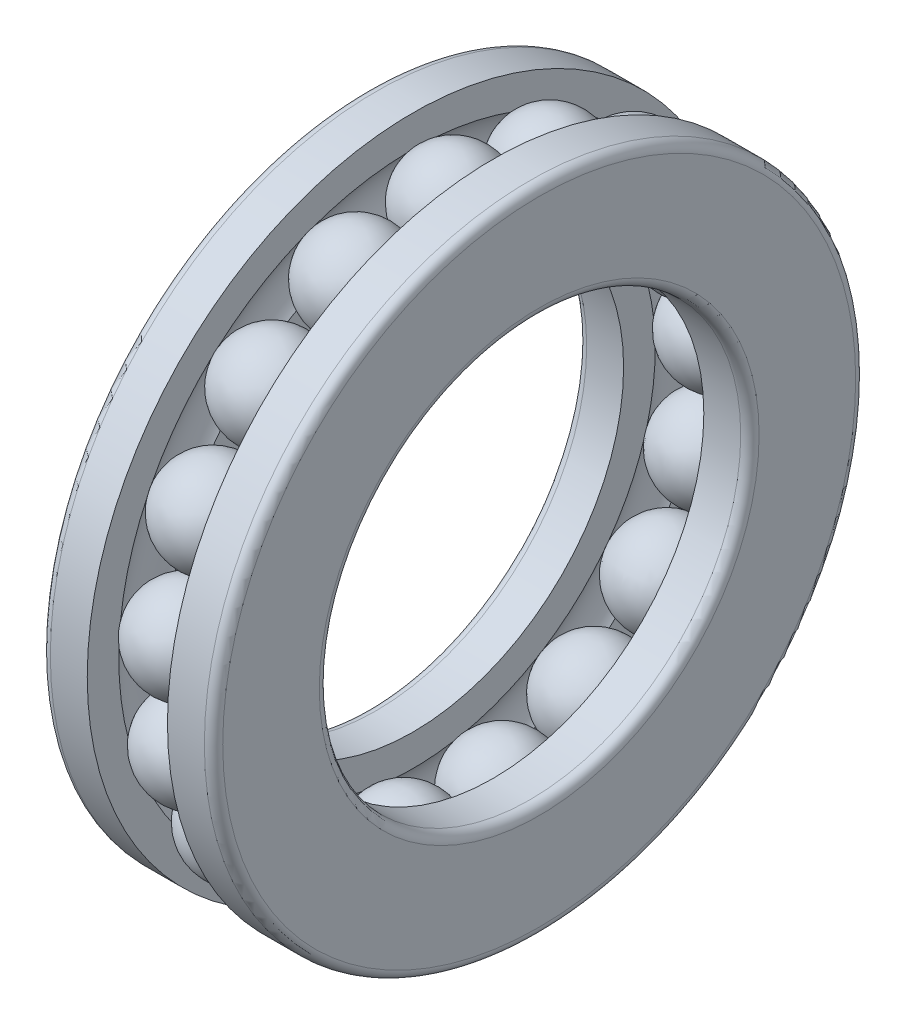
SolidWorks part; units mm, degrees
ref_plane "Plane1" through (0, 0, 0) normal (0, 0, 1) x (1, 0, 0)
ref_plane "Plane2" through (0, 0, 0) normal (0, 1, 0) x (1, 0, 0)
ref_plane "Plane3" through (0, 0, 0) normal (1, 0, 0) x (0, 0, -1)
sketch "Clipboard" plane through (0, 0, 0) normal (0, 0, 1) x (1, 0, 0)
  line L0 (-10, 0) -> (10, 0) construction
  line L1 (0, 0) -> (21.3836, -6.5376)
  line L2 (0, 0) -> (27.3662, 35.0271)
  line L3 (0, 0) -> (13.7666, -17.6205)
  line L4 (0, 0) -> (-22.3471, -0.7804)
  dimension "BallCLRad" = 44.45
  dimension "Count" = 52
  dimension "Show_count" = 52
  dimension "Max_count" = 17
  dimension "Min_count" = 2
sketch "InnRacSke" plane through (0, 0, 0) normal (0, 0, 1) x (1, 0, 0)
  line L0 (-6.6469, 40.1581) -> (-6.6469, 34.925)
  line L1 (-6.6469, 34.925) -> (-12.7635, 34.925)
  line L2 (-14.2875, 36.449) -> (-14.2875, 52.451)
  line L3 (-12.7635, 53.975) -> (-6.6469, 53.975)
  line L4 (-6.6469, 53.975) -> (-6.6469, 48.7419)
  line L5 (-34.925, 0) -> (34.925, 0) construction
  line L6 (0, 0) -> (0, 25.4) construction
  arc A0 (-12.7635, 34.925) -> (-14.2875, 36.449) centre (-12.7635, 36.449) cw
  arc A1 (-14.2875, 52.451) -> (-12.7635, 53.975) centre (-12.7635, 52.451) cw
  arc A2 (-6.6469, 48.7419) -> (-6.6469, 40.1581) centre (0, 44.45) ccw
  dimension "BallCLRad" = 44.45
  dimension "Ball_diameter" = 15.8242
  dimension "ID" = 69.85
  dimension "OD" = 107.95
  dimension "Width" = 28.575
  dimension "gap" = 13.2937
revolve "Race" add sketch "InnRacSke" angle 360 about L5
ref_axis "Axis1" through (-50, 0, 0) along (1, 0, 0)
sketch "BalDetSke" plane through (0, 0, 0) normal (0, 0, 1) x (1, 0, 0)
  line L0 (-7.9375, 44.45) -> (7.9375, 44.45)
  line L1 (-14.5732, 44.45) -> (14.5732, 44.45) construction
  arc A0 (7.9375, 44.45) -> (-7.9375, 44.45) centre (0, 44.45) cw
  dimension "BallCLRad" = 44.45
  dimension "Ball_diameter" = 15.875
revolve "BallDetailed" add sketch "BalDetSke" angle 360 about L1
sketch "BalSimSke" plane through (0, 0, 0) normal (0, 0, 1) x (1, 0, 0)
  line L0 (-25.4, 0) -> (25.4, 0) construction
  circle A0 centre (0, 44.45) radius 7.9375
  dimension "BallCLRad" = 44.45
  dimension "Ball_diameter" = 15.875
revolve "BallsSimplified" [suppressed] add sketch "BalSimSke" angle 360 about L0
mirror "Mirror1" about plane through (0, 0, 0) normal (1, 0, 0) of "Race"
pattern_circular "BallsDetailed" count 17 every 21.176 about axis through (-50, 0, 0) along (1, 0, 0) of "BallDetailed"
sketch "CagSpiSke" plane through (0, 0, 0) normal (0, 0, 1) x (1, 0, 0)
  line L0 (1.9844, 35.7188) -> (1.9844, 53.1812)
  line L1 (1.9844, 53.1812) -> (-1.9844, 53.1812)
  line L2 (-1.9844, 53.1812) -> (-1.9844, 35.7188)
  line L3 (-1.9844, 35.7188) -> (1.9844, 35.7188)
  line L4 (-34.925, 0) -> (34.925, 0) construction
  line L5 (0, 0) -> (0, 50.8) construction
  dimension "Thickness" = 3.9688
  dimension "ID" = 71.4375
  dimension "OD" = 106.3625
revolve "CageSpine" [suppressed] add sketch "CagSpiSke" angle 360 about L4
equation "\"BallCLRad@Clipboard\" =  ( \"OD@InnRacSke\" + \"ID@InnRacSke\" )  / 4"
equation "\"BallCLRad@BalSimSke\" = \"BallCLRad@Clipboard\""
equation "\"BallCLRad@BalDetSke\" = \"BallCLRad@Clipboard\""
equation "\"BallCLRad@InnRacSke\" = \"BallCLRad@Clipboard\""
equation "\"Ball_diameter@InnRacSke\" = \"Ball_diameter@BalDetSke\" - 0.002"
equation "\"Ball_diameter@BalSimSke\" = \"Ball_diameter@BalDetSke\""
equation "\"Max_count@Clipboard\" = int( 3.14159265 / atn(( \"Ball_diameter@BalDetSke\" / 2) / sqr( \"BallCLRad@Clipboard\"  *  \"BallCLRad@Clipboard\" - ( \"Ball_diameter@BalDetSke\" / 2) *  ( \"Ball_diameter@BalDetSke\" / 2))))"
equation "\"Max_count@Clipboard\" = ((sgn( \"Max_count@Clipboard\" - \"Count@Clipboard\" )-1)*( \"Max_count@Clipboard\" - \"Count@Clipboard\" ))/-2+ \"Count@Clipboard\""
equation "\"Count@BallsDetailed\" = int( \"Show_count@Clipboard\" ) "
equation "\"Count@BallsDetailed\" = ((sgn( \"Count@BallsDetailed\" - \"Max_count@Clipboard\" )-1)*( \"Count@BallsDetailed\" - \"Max_count@Clipboard\" ))/-2+ \"Max_count@Clipboard\""
equation "\"Count@BallsDetailed\" = ((sgn( \"Count@BallsDetailed\" - \"Min_count@Clipboard\" )+1)*( \"Count@BallsDetailed\" - \"Min_count@Clipboard\"))/2 +\"Min_count@Clipboard\""
equation "\"Angle@BallsDetailed\" = 360.0 / \"Max_count@Clipboard\""
equation "\"Angle@CageSpine\" =  \"Angle@BallsDetailed\" * ( \"Count@BallsDetailed\" -1 + int( \"Count@BallsDetailed\" / \"Max_count@Clipboard\" ) )  + 0.001 -  int( \"Count@BallsDetailed\" / \"Max_count@Clipboard\" ) * 0.001"
equation "\"Angle@CageSpine\" =  \"Angle@CageSpine\" * int( \"Min_count@Clipboard\" / 2) + int(1 / \"Min_count@Clipboard\")  * 0.001"
equation "\"Thickness@CagSpiSke\" =  \"Ball_diameter@BalDetSke\" * 0.25"
equation "\"OD@CagSpiSke\" = ( \"OD@InnRacSke\" + ( \"BallCLRad@Clipboard\" * 2 + \"Ball_diameter@BalDetSke\" )) / 2"
equation "\"ID@CagSpiSke\" = ( \"ID@InnRacSke\" + ( \"BallCLRad@Clipboard\" * 2 - \"Ball_diameter@BalDetSke\" )) / 2"
